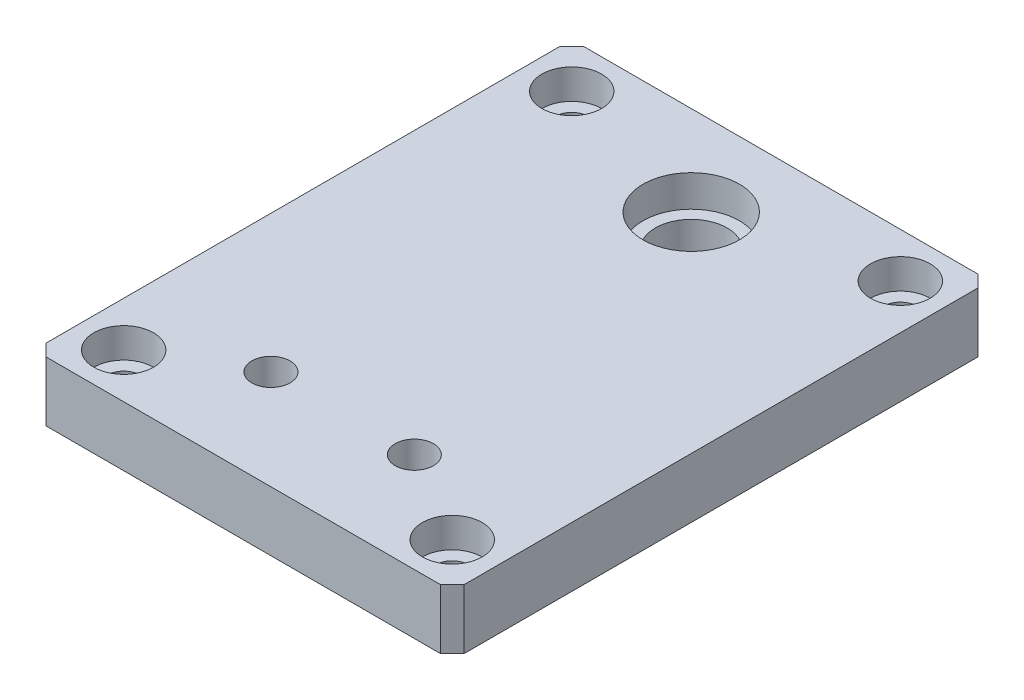
SolidWorks part; units mm, degrees
ref_plane "Front Plane" through (0, 0, 0) normal (0, 0, 1) x (1, 0, 0)
ref_plane "Top Plane" through (0, 0, 0) normal (0, 1, 0) x (1, 0, 0)
ref_plane "Right Plane" through (0, 0, 0) normal (1, 0, 0) x (0, 0, -1)
sketch "Sketch1" plane through (0, 0, 0) normal (0, 1, 0) x (1, 0, 0)
  line L1 (-35, -45) -> (35, -45)
  line L2 (-35, -45) -> (-35, 45)
  line L3 (-35, 45) -> (35, 45)
  line L4 (35, -45) -> (35, 45)
  line L5 (-35, -45) -> (35, 45) construction
  line L6 (-35, 45) -> (35, -45) construction
  point P0 (0, 0)
  dimension "D1" = 70
  dimension "D2" = 90
extrude "Boss-Extrude1" add sketch "Sketch1" along normal blind 10
sketch "Sketch4" plane through (0, 10, 0) normal (0, 1, 0) x (1, 0, 0)
  line L0 (-35, 45) -> (-35, -45) construction
  line L1 (35, 45) -> (-35, 45) construction
  line L3 (35, -45) -> (35, 45) construction
  line L4 (-35, -45) -> (35, -45) construction
  point P0 (-27.5, -37.5)
  point P2 (-27.5, 37.5)
  point P4 (27.5, 37.5)
  point P6 (27.5, -37.5)
  dimension "D1" = 7.5
  dimension "D2" = 7.5
  dimension "D3" = 7.5
  dimension "D4" = 7.5
hole_wizard "CBORE for M5 SHCS1" positions "Sketch4" profile "Sketch3" counterbore size "M5" standard "ANSI Metric" end condition through all
sketch "Sketch3" plane through (-27.5, 10, 37.5) normal (1, 0, 0) x (0, 0, 1)
  line L0 (0, 0) -> (0, 10)
  line L1 (0, 10) -> (2.75, 10)
  line L3 (2.75, 10) -> (2.75, 5)
  line L4 (2.75, 5) -> (5, 5)
  line L5 (5, 5) -> (5, 0)
  line L7 (5, 0) -> (0, 0)
  line L11 (0, -6.35) -> (0, 107.95) construction
  dimension "Thru Hole Dia." = 5.5
  dimension "Thru Hole Depth" = 10
  dimension "C'Bore Dia." = 10
  dimension "C'Bore Depth" = 5
sketch "Sketch7" plane through (0, 10, 0) normal (0, 1, 0) x (1, 0, 0)
  line L0 (35, 45) -> (-35, 45) construction
  point P0 (0, 30)
  dimension "D1" = 15
hole_wizard "Ø1.0mm Dowel Hole1" positions "Sketch7" profile "Sketch6" hole size "Ø1.0" standard "ANSI Metric"
sketch "Sketch6" plane through (0, 10, -30) normal (1, 0, 0) x (0, 0, 1)
  line L0 (0, 0) -> (0, 5.3)
  line L1 (0, 5.3) -> (8.075, 5.3)
  line L2 (8.075, 5.3) -> (8.075, 0)
  line L5 (8.075, 0) -> (0, 0)
  line L10 (0, 5.3) -> (-8.075, 5.3) construction
  line L11 (0, -6.35) -> (0, 107.95) construction
  dimension "Hole Dia." = 16.15
  dimension "Hole Depth" = 5.3
  dimension "Drill Angle" = 180
sketch "Sketch13" plane through (0, 4.7, 0) normal (0, 1, 0) x (1, 0, 0)
  point P0 (0, 30)
hole_wizard "Ø1.0mm Dowel Hole3" positions "Sketch13" profile "Sketch12" hole size "Ø1.0" standard "ANSI Metric" end condition through all
sketch "Sketch12" plane through (0, 4.7, -30) normal (1, 0, 0) x (0, 0, 1)
  line L0 (0, 0) -> (0, 4.7)
  line L1 (0, 4.7) -> (6, 4.7)
  line L2 (6, 4.7) -> (6, 0)
  line L5 (6, 0) -> (0, 0)
  line L11 (0, -6.35) -> (0, 107.95) construction
  dimension "Thru Hole Dia." = 12
  dimension "Thru Hole Depth" = 4.7
sketch "Sketch14" plane through (0, 10, 0) normal (0, 1, 0) x (1, 0, 0)
  circle A2 centre (12, -28.35) radius 3.2
  circle A3 centre (-12, -28.35) radius 3.2
  dimension "D5" = 6.4
  dimension "D6" = 6.4
  dimension "D1" = 28.35
  dimension "D2" = 12
  dimension "D3" = 12
  dimension "D4" = 28.35
extrude "Cut-Extrude1" cut sketch "Sketch14" against normal through all
chamfer "Chamfer1" distance 2 angle 45 4 edges at (35, 5, 45) (35, 5, -45) (-35, 5, -45) (-35, 5, 45)
equation "\"D1@Sketch4\" = 5 * 1.5"
equation "\"D2@Sketch4\" = \"D1@Sketch4\""
equation "\"D4@Sketch14\"=\"D1@Sketch14\""
